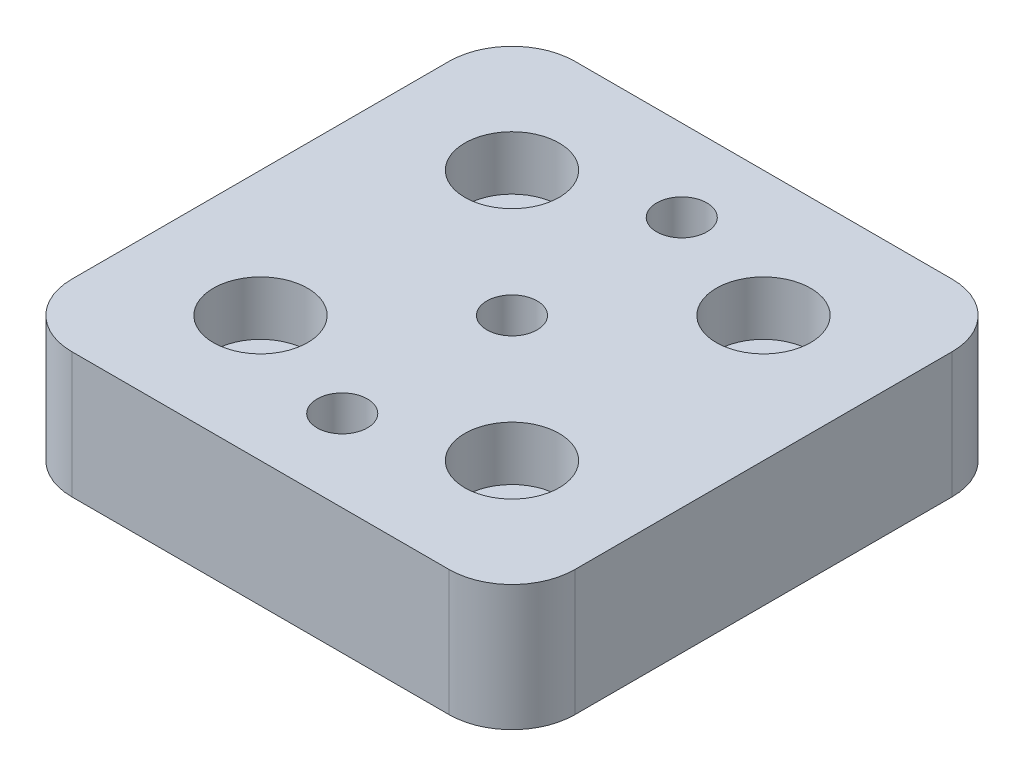
SolidWorks part; units mm, degrees
ref_plane "Płaszczyzna przednia" through (0, 0, 0) normal (0, 0, 1) x (1, 0, 0)
ref_plane "Płaszczyzna górna" through (0, 0, 0) normal (0, 1, 0) x (1, 0, 0)
ref_plane "Płaszczyzna prawa" through (0, 0, 0) normal (1, 0, 0) x (0, 0, -1)
sketch "Szkic1" plane through (0, 0, 0) normal (0, 1, 0) x (1, 0, 0)
  line L1 (-40, -40) -> (40, -40)
  line L2 (-40, -40) -> (-40, 40)
  line L3 (-40, 40) -> (40, 40)
  line L4 (40, -40) -> (40, 40)
  line L5 (-40, -40) -> (40, 40) construction
  line L6 (-40, 40) -> (40, -40) construction
  point P0 (0, 0)
  dimension "D1" = 80
  dimension "D2" = 80
extrude "Dodanie-wyciągnięcie1" add sketch "Szkic1" along normal blind 20
sketch "Szkic2" plane through (0, 20, 0) normal (0, 1, 0) x (1, 0, 0)
  line L0 (0, 56.7752) -> (0, -75.6681) construction
  line L1 (-69.0171, 0) -> (110.4658, 0) construction
  circle A0 centre (-20, 20) radius 4
  circle A1 centre (20, 20) radius 4
  circle A2 centre (20, -20) radius 4
  circle A3 centre (-20, -20) radius 4
  circle A5 centre (0, 0) radius 4
  circle A6 centre (0, -27) radius 4
  circle A7 centre (0, 27) radius 4
  dimension "D1" = 8
  dimension "D5" = 8
  dimension "D6" = 8
  dimension "D2" = 40
  dimension "D3" = 40
  dimension "D7" = 54
hole_wizard "Pogłębienie walcowe pod M8 Wkręt z łbem walcowym z gniazdem sześciokątnym1" positions "Szkic3" profile "Szkic4" counterbore size "M8" standard "ISO" end condition through all
sketch "Szkic3" plane through (0, 20, 0) normal (0, 1, 0) x (1, 0, 0)
  point P0 (-20, 20)
  point P3 (20, 20)
  point P6 (20, -20)
  point P9 (-20, -20)
sketch "Szkic4" plane through (-20, 20, -20) normal (1, 0, 0) x (0, 0, 1)
  line L0 (0, 0) -> (0, 20)
  line L1 (0, 20) -> (4.5, 20)
  line L3 (4.5, 20) -> (4.5, 8.6)
  line L4 (4.5, 8.6) -> (7.5, 8.6)
  line L5 (7.5, 8.6) -> (7.5, 0)
  line L7 (7.5, 0) -> (0, 0)
  line L11 (0, -6.35) -> (0, 107.95) construction
  dimension "Średnica otworu na wylot" = 9
  dimension "Głębokość otworu na wylot" = 20
  dimension "Średnica pogłębienia walcowego" = 15
  dimension "Głębokość pogłębienia walcowego" = 8.6
hole_wizard "Otwory ustalające Ø8.0mm1" positions "Szkic5" profile "Szkic6" hole size "Ø8.0" standard "ISO" end condition through all
sketch "Szkic5" plane through (0, 20, 0) normal (0, 1, 0) x (1, 0, 0)
  point P0 (0, 27)
  point P3 (0, 0)
  point P6 (0, -27)
sketch "Szkic6" plane through (0, 20, -27) normal (1, 0, 0) x (0, 0, 1)
  line L0 (0, 0) -> (0, 20)
  line L1 (0, 20) -> (4, 20)
  line L2 (4, 20) -> (4, 0)
  line L5 (4, 0) -> (0, 0)
  line L11 (0, -6.35) -> (0, 107.95) construction
  dimension "Średnica otworu na wylot" = 8
  dimension "Głębokość otworu na wylot" = 20
fillet "Zaokrąglenie1" radius 10 4 edges at (40, 10, -40) (-40, 10, -40) (-40, 10, 40) (40, 10, 40)
